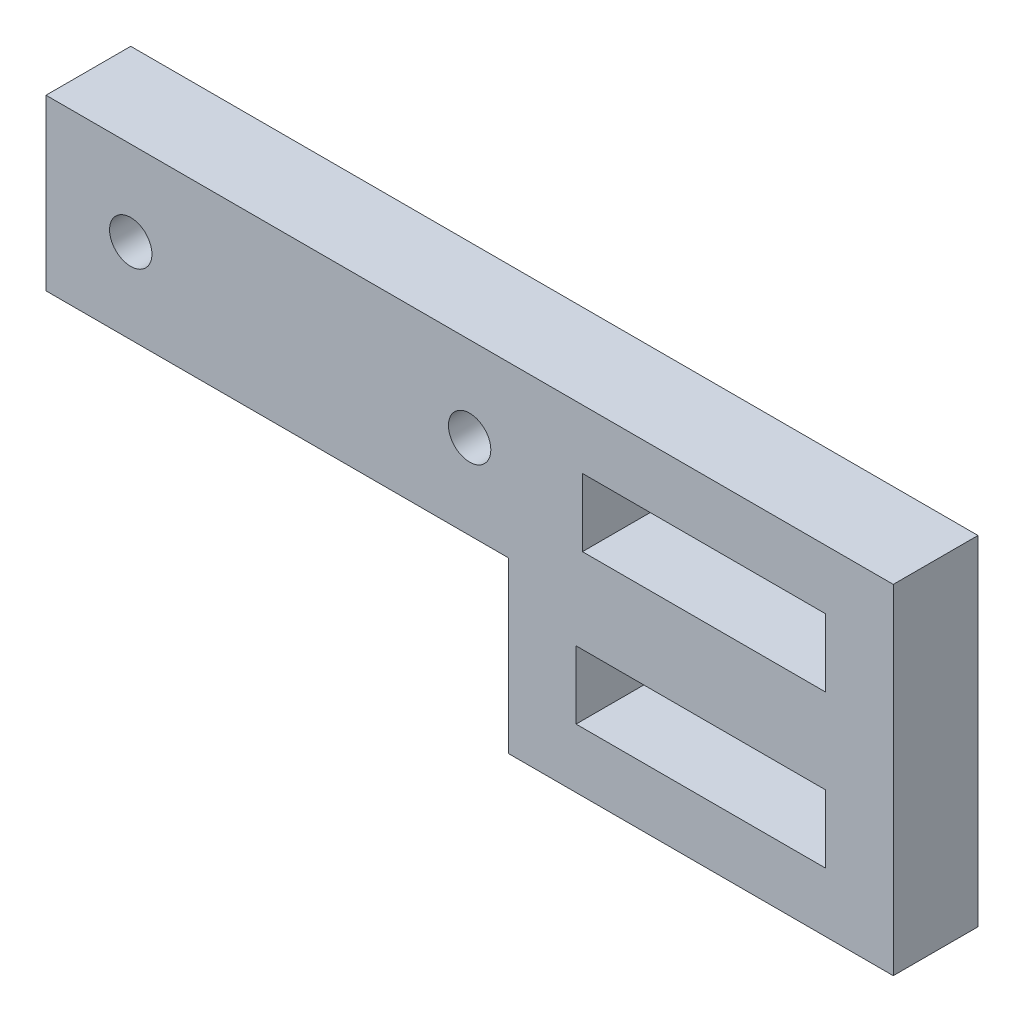
SolidWorks part; units mm, degrees
ref_plane "Front Plane" through (0, 0, 0) normal (0, 0, 1) x (1, 0, 0)
ref_plane "Top Plane" through (0, 0, 0) normal (0, 1, 0) x (1, 0, 0)
ref_plane "Right Plane" through (0, 0, 0) normal (1, 0, 0) x (0, 0, -1)
sketch "Sketch1" plane through (0, 0, 0) normal (0, 0, 1) x (1, 0, 0)
  line L0 (-30.2835, 4.3155) -> (33.2165, 4.3155)
  line L1 (33.2165, 4.3155) -> (33.2165, -21.0845)
  line L2 (33.2165, -21.0845) -> (4.3632, -21.0845)
  line L3 (4.3632, -21.0845) -> (4.3632, -8.3845)
  line L4 (4.3632, -8.3845) -> (-30.2835, -8.3845)
  line L5 (-30.2835, -8.3845) -> (-30.2835, 4.3155)
  dimension "D1" = 63.5
  dimension "D2" = 25.4
  dimension "D3" = 12.7
extrude "Boss-Extrude1" add sketch "Sketch1" along normal blind 6.35
sketch "Sketch2" plane through (0, 0, 6.35) normal (0, 0, 1) x (1, 0, 0)
  line L0 (33.2165, 4.3155) -> (-30.2835, 4.3155) construction
  line L1 (9.9217, -0.1295) -> (28.1365, -0.1295)
  line L2 (9.9217, -0.1295) -> (9.9217, -5.2095)
  line L3 (9.9217, -5.2095) -> (28.1365, -5.2095)
  line L4 (28.1365, -0.1295) -> (28.1365, -5.2095)
  line L5 (9.4432, -11.5595) -> (28.1365, -11.5595)
  line L6 (9.4432, -11.5595) -> (9.4432, -16.6395)
  line L7 (9.4432, -16.6395) -> (28.1365, -16.6395)
  line L8 (28.1365, -11.5595) -> (28.1365, -16.6395)
  line L9 (-30.2835, 4.3155) -> (-30.2835, -8.3845) construction
  line L10 (4.3632, -21.0845) -> (33.2165, -21.0845) construction
  line L11 (4.3632, -8.3845) -> (4.3632, -21.0845) construction
  line L12 (33.2165, -21.0845) -> (33.2165, 4.3155) construction
  circle A0 centre (-23.9335, -2.0345) radius 1.5875
  circle A1 centre (1.4665, -2.0345) radius 1.5875
  point P12 (0, 0)
  dimension "D2" = 3.175
  dimension "D1" = 25.4
  dimension "D3" = 6.35
  dimension "D4" = 6.35
  dimension "D5" = 4.445
  dimension "D6" = 4.445
  dimension "D7" = 5.08
  dimension "D8" = 5.08
  dimension "D9" = 5.08
extrude "Cut-Extrude1" cut sketch "Sketch2" against normal blind 6.35
